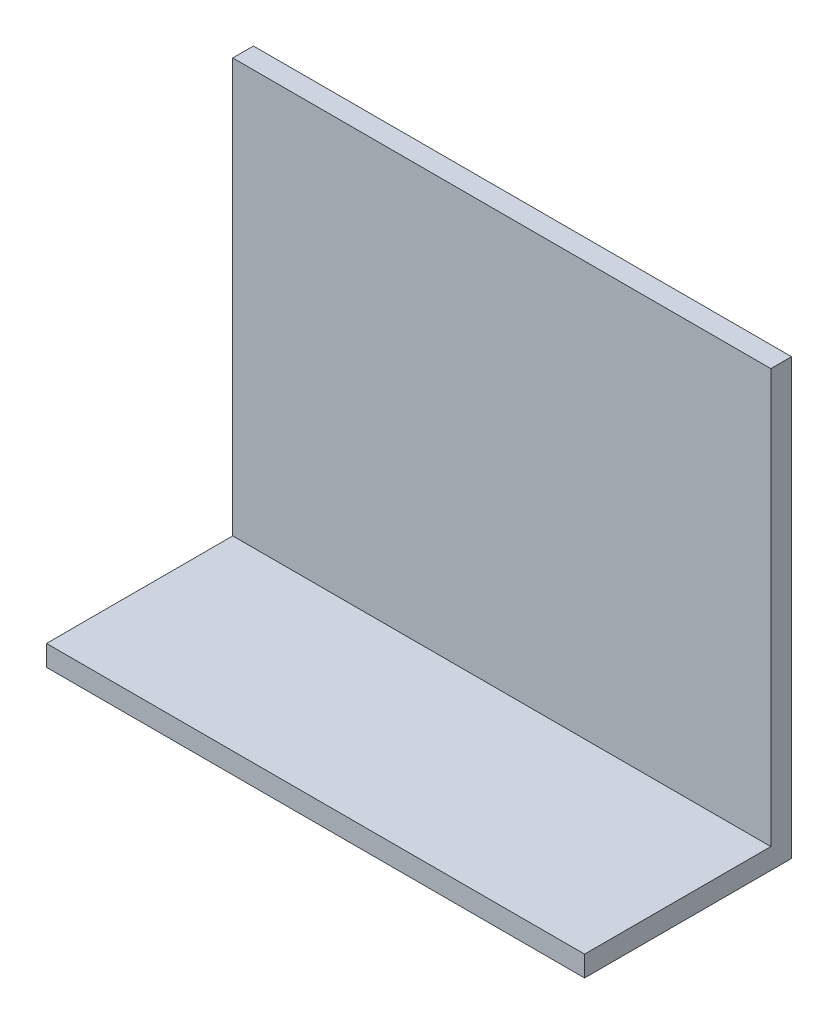
SolidWorks part; units mm, degrees
ref_plane "Plan de face" through (0, 0, 0) normal (0, 0, 1) x (1, 0, 0)
ref_plane "Plan de dessus" through (0, 0, 0) normal (0, 1, 0) x (1, 0, 0)
ref_plane "Plan de droite" through (0, 0, 0) normal (1, 0, 0) x (0, 0, -1)
sketch "Esquisse1" plane through (0, 0, 0) normal (0, 0, 1) x (1, 0, 0)
  line L1 (-26, -21) -> (26, -21)
  line L2 (-26, -21) -> (-26, 21)
  line L3 (-26, 21) -> (26, 21)
  line L4 (26, -21) -> (26, 21)
  line L5 (-26, -21) -> (26, 21) construction
  line L6 (-26, 21) -> (26, -21) construction
  point P0 (0, 0)
  dimension "D1" = 52
  dimension "D2" = 42
extrude "Boss.-Extru.1" add sketch "Esquisse1" along normal blind 20
sketch "Esquisse2" plane through (0, 21, 0) normal (0, 1, 0) x (1, 0, 0)
  line L8 (24, -2) -> (-24, -2)
  line L9 (-24, -2) -> (-24, -18)
  line L10 (-24, -18) -> (24, -18)
  line L11 (24, -18) -> (24, -2)
  line L12 (34.4102, -2) -> (-31.5984, -2)
  line L13 (-31.5984, -2) -> (-31.5984, -42.9462)
  line L14 (-31.5984, -42.9462) -> (34.4102, -42.9462)
  line L15 (34.4102, -42.9462) -> (34.4102, -2)
  dimension "D1" = 2
extrude "Enlèv. mat.-Extru.1" cut sketch "Esquisse2" against normal blind 40
